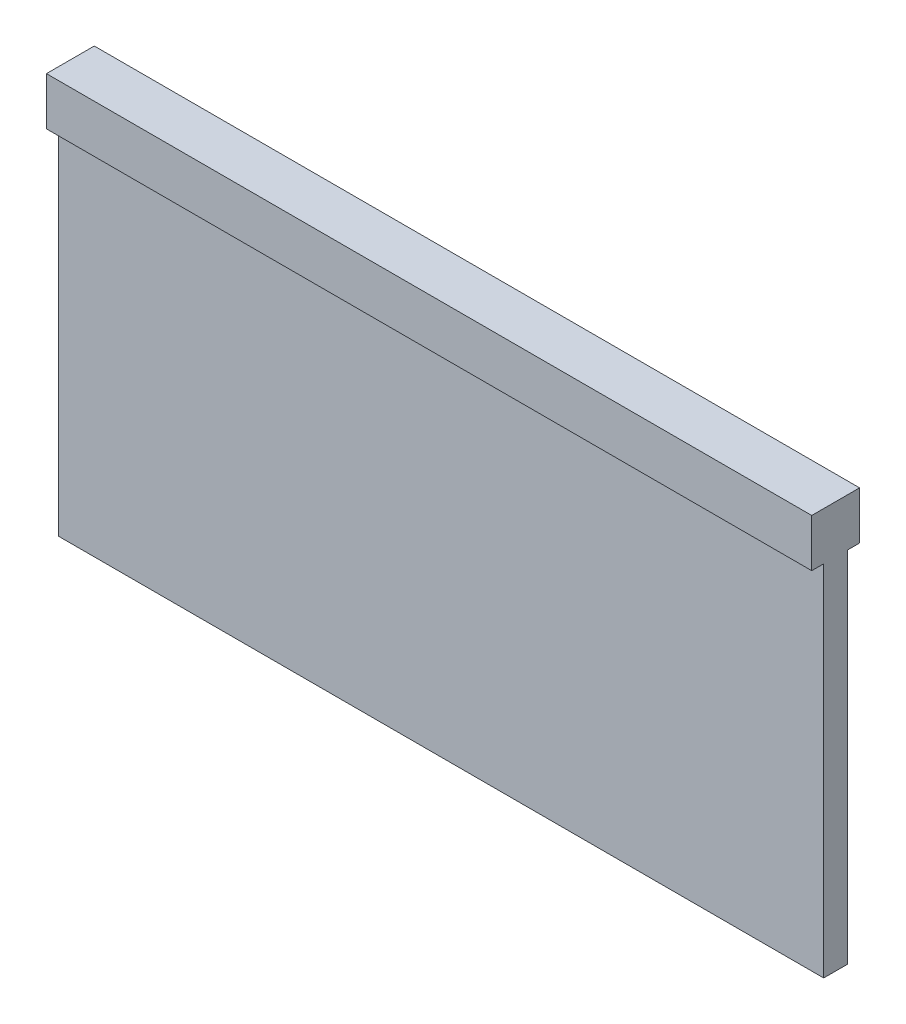
SolidWorks part; units mm, degrees
material "2024 Alloy"
ref_plane "Front Plane" through (0, 0, 0) normal (0, 0, 1) x (1, 0, 0)
ref_plane "Top Plane" through (0, 0, 0) normal (0, 1, 0) x (1, 0, 0)
ref_plane "Right Plane" through (0, 0, 0) normal (1, 0, 0) x (0, 0, -1)
sketch "Sketch1" plane through (0, 0, 0) normal (0, 0, 1) x (1, 0, 0)
  line L1 (-203.2, 107.95) -> (203.2, 107.95)
  line L2 (-203.2, 107.95) -> (-203.2, -107.95)
  line L3 (-203.2, -107.95) -> (203.2, -107.95)
  line L4 (203.2, 107.95) -> (203.2, -107.95)
  line L5 (-203.2, 107.95) -> (203.2, -107.95) construction
  line L6 (-203.2, -107.95) -> (203.2, 107.95) construction
  point P4 (0, 0)
  point P8 (-203.2, 0)
  dimension "D1" = 406.4
  dimension "D2" = 215.9
extrude "Boss-Extrude1" add sketch "Sketch1" along normal mid plane 25.4
sketch "Sketch3" plane through (0, 0, 12.7) normal (0, 0, 1) x (1, 0, 0)
  line L0 (-203.2, 107.95) -> (-203.2, -107.95) construction
  line L1 (-203.2, 82.55) -> (203.2, 82.55)
  line L2 (-203.2, 82.55) -> (-203.2, -107.95)
  line L3 (-203.2, -107.95) -> (203.2, -107.95)
  line L4 (203.2, 82.55) -> (203.2, -107.95)
  line L5 (-203.2, 82.55) -> (203.2, -107.95) construction
  line L6 (-203.2, -107.95) -> (203.2, 82.55) construction
  line L7 (203.2, 107.95) -> (-203.2, 107.95) construction
  point P4 (0, -12.7)
  dimension "D1" = 25.4
extrude "Cut-Extrude1" cut sketch "Sketch3" against normal blind 6.35
mirror "Mirror1" about plane through (0, 0, 0) normal (0, 0, 1) of "Cut-Extrude1"
